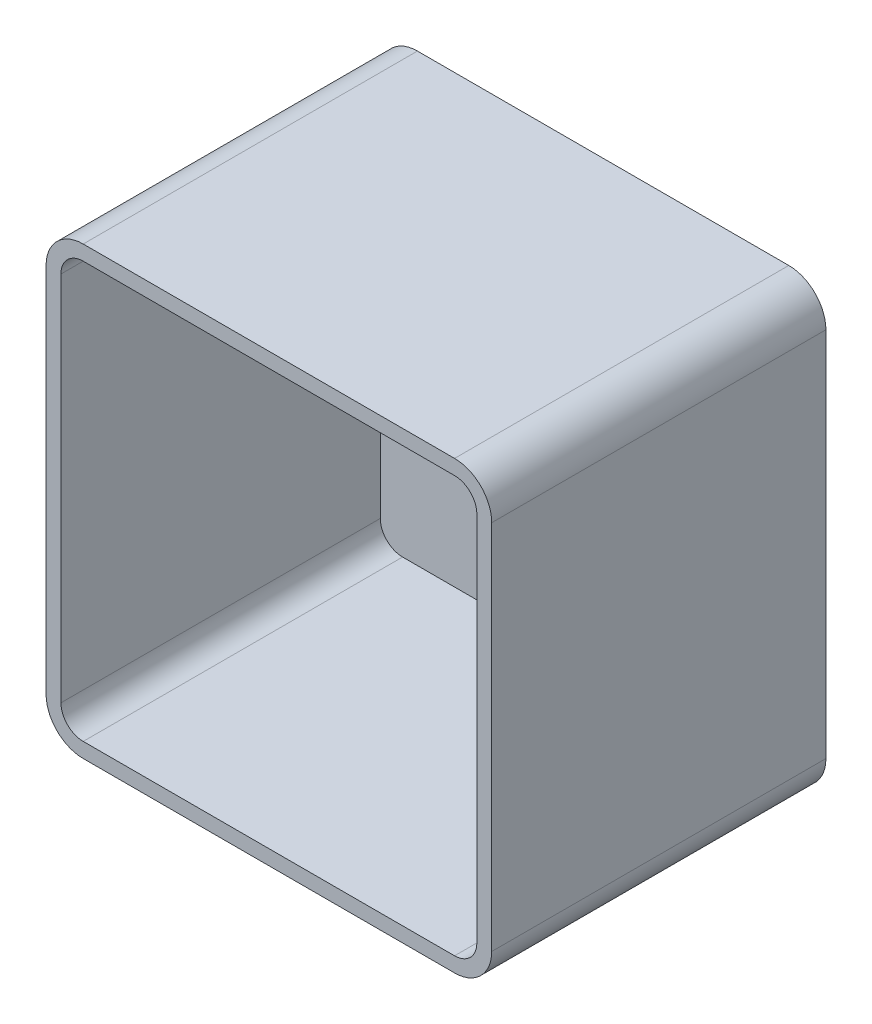
SolidWorks part; units mm, degrees
ref_plane "Front Plane" through (0, 0, 0) normal (0, 0, 1) x (1, 0, 0)
ref_plane "Top Plane" through (0, 0, 0) normal (0, 1, 0) x (1, 0, 0)
ref_plane "Right Plane" through (0, 0, 0) normal (1, 0, 0) x (0, 0, -1)
sketch "Sketch1" plane through (0, 0, 0) normal (0, 0, 1) x (1, 0, 0)
  line L1 (-39.9038, 25.9719) -> (80.0962, 25.9719)
  line L2 (-39.9038, 25.9719) -> (-39.9038, -94.0281)
  line L3 (-39.9038, -94.0281) -> (80.0962, -94.0281)
  line L4 (80.0962, 25.9719) -> (80.0962, -94.0281)
  dimension "D1" = 120
  dimension "D2" = 120
extrude "Boss-Extrude1" add sketch "Sketch1" along normal blind 90
fillet "Fillet1" radius 10 4 edges at (-39.9038, -94.0281, 45) (80.0962, -94.0281, 45) (-39.9038, 25.9719, 45) (80.0962, 25.9719, 45)
shell "Shell1" thickness 4
sketch "Sketch2" plane through (0, 0, 90) normal (0, 0, 1) x (1, 0, 0)
  line L0 (-37.9038, 15.9719) -> (-37.9038, -84.0281)
  line L1 (-29.9038, -92.0281) -> (70.0962, -92.0281)
  line L2 (78.0962, -84.0281) -> (78.0962, 15.9719)
  line L3 (70.0962, 23.9719) -> (-29.9038, 23.9719)
  line L4 (-39.9038, 15.9719) -> (-39.9038, -84.0281)
  line L5 (-29.9038, -94.0281) -> (70.0962, -94.0281)
  line L6 (80.0962, -84.0281) -> (80.0962, 15.9719)
  line L7 (70.0962, 25.9719) -> (-29.9038, 25.9719)
  line L8 (-39.9038, 15.9719) -> (-39.9038, -84.0281)
  line L9 (-29.9038, -94.0281) -> (70.0962, -94.0281)
  line L10 (80.0962, -84.0281) -> (80.0962, 15.9719)
  line L11 (70.0962, 25.9719) -> (-29.9038, 25.9719)
  arc A0 (-37.9038, -84.0281) -> (-29.9038, -92.0281) centre (-29.9038, -84.0281) ccw
  arc A1 (70.0962, -92.0281) -> (78.0962, -84.0281) centre (70.0962, -84.0281) ccw
  arc A2 (78.0962, 15.9719) -> (70.0962, 23.9719) centre (70.0962, 15.9719) ccw
  arc A3 (-29.9038, 23.9719) -> (-37.9038, 15.9719) centre (-29.9038, 15.9719) ccw
  arc A4 (-39.9038, -84.0281) -> (-29.9038, -94.0281) centre (-29.9038, -84.0281) ccw
  arc A5 (70.0962, -94.0281) -> (80.0962, -84.0281) centre (70.0962, -84.0281) ccw
  arc A6 (80.0962, 15.9719) -> (70.0962, 25.9719) centre (70.0962, 15.9719) ccw
  arc A7 (-29.9038, 25.9719) -> (-39.9038, 15.9719) centre (-29.9038, 15.9719) ccw
  arc A8 (-39.9038, -84.0281) -> (-29.9038, -94.0281) centre (-29.9038, -84.0281) ccw
  arc A9 (70.0962, -94.0281) -> (80.0962, -84.0281) centre (70.0962, -84.0281) ccw
  arc A10 (80.0962, 15.9719) -> (70.0962, 25.9719) centre (70.0962, 15.9719) ccw
  arc A11 (-29.9038, 25.9719) -> (-39.9038, 15.9719) centre (-29.9038, 15.9719) ccw
  dimension "D1" = 0
  dimension "D2" = 2
